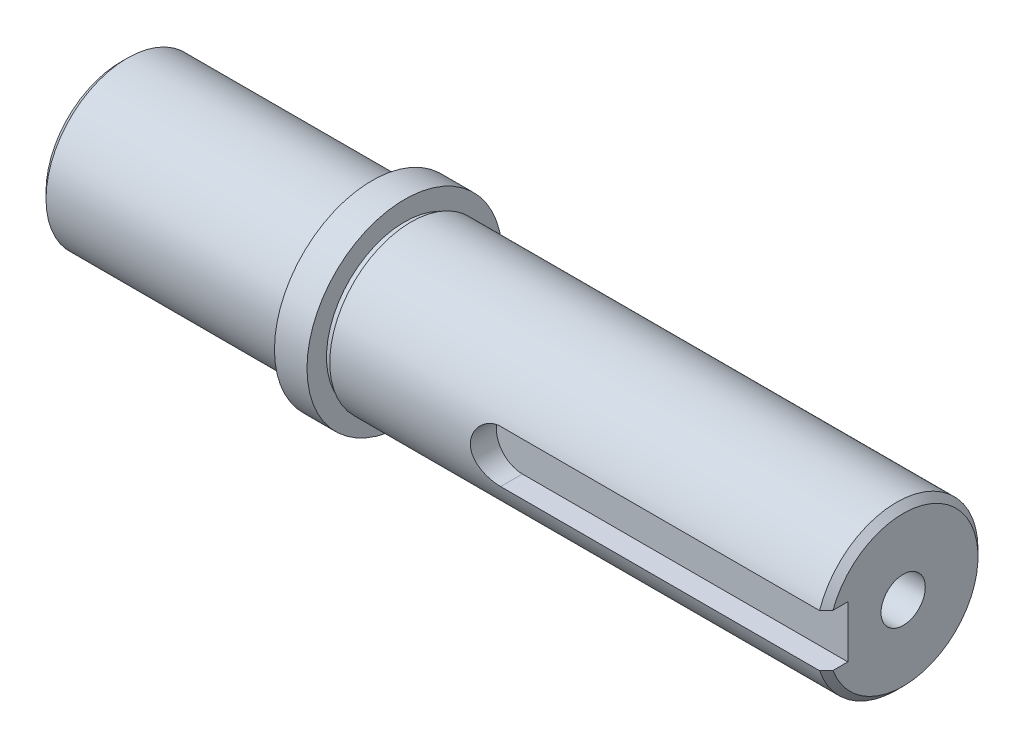
SolidWorks part; units mm, degrees
ref_plane "Plano frontal" through (0, 0, 0) normal (0, 0, 1) x (1, 0, 0)
ref_plane "Plano superior" through (0, 0, 0) normal (0, 1, 0) x (1, 0, 0)
ref_plane "Plano direito" through (0, 0, 0) normal (1, 0, 0) x (0, 0, -1)
sketch "Sketch1" plane through (0, 0, 0) normal (0, 0, 1) x (1, 0, 0)
  line L0 (0, 0) -> (0, 12.5)
  line L1 (0, 12.5) -> (38.6, 12.5)
  line L2 (38.6, 12.5) -> (38.6, 15)
  line L3 (38.6, 15) -> (43.6, 15)
  line L4 (43.6, 15) -> (43.6, 12)
  line L5 (43.6, 12) -> (44.6, 12)
  line L6 (44.6, 12) -> (44.6, 12.5)
  line L7 (44.6, 12.5) -> (120.2, 12.5)
  line L8 (120.2, 12.5) -> (120.2, 0)
  line L9 (120.2, 0) -> (0, 0)
  line L11 (0, 0) -> (-21.8278, 0) construction
  dimension "D1" = 25
  dimension "D2" = 38.6
  dimension "D3" = 5
  dimension "D4" = 1
  dimension "D5" = 24
  dimension "D6" = 76.6
  dimension "D7" = 30
revolve "Revolve1" add sketch "Sketch1" angle 360 about L11
chamfer "Chamfer1" distance 1 angle 45 1 edges at (0, 0, -12.5)
sketch "Sketch2" plane through (120.2, 4.6196, 5.8725) normal (1, 0, 0) x (0, 0, -1)
  line L0 (-6.6275, -4.6196) -> (5.8725, -4.6196) construction
  line L1 (5.8725, -4.6196) -> (5.8725, 7.8804) construction
  circle A0 centre (5.8725, -4.6196) radius 12.5 construction
  circle A2 centre (5.8725, -4.6196) radius 12.5
  dimension "Angle from vertical" = 270
ref_plane "Plane1" through (120.2, 0, 12.5) normal (0, 0, -1) x (-1, 0, 0)
sketch "Sketch3" plane through (120.2, 2.9363, 12.5) normal (0, 0, -1) x (1, 0, 0)
  line L0 (-5, 2.9363) -> (-50, 2.9363) construction
  line L1 (-5, 6.9363) -> (-50, 6.9363)
  line L2 (-5, -1.0637) -> (-50, -1.0637)
  arc A0 (-5, 6.9363) -> (-5, -1.0637) centre (-5, 2.9363) cw
  arc A1 (-50, 6.9363) -> (-50, -1.0637) centre (-50, 2.9363) ccw
  dimension "Keyway width" = 8
  dimension "Distance from end face" = 5
  dimension "Length of slot" = 45
extrude "Cut-Extrude1" cut sketch "Sketch3" along normal blind 4
other "keyway (bs 4235 - part i)<1>"
sketch "Sketch4" plane through (120.2, 0, 0) normal (1, 0, 0) x (0, 0, -1)
  line L0 (-8.5, 4) -> (-11.8427, 4) construction
  line L1 (-8.5, 4) -> (-11.8427, 4)
  line L2 (-8.5, 4) -> (-8.5, -4) construction
  line L3 (-8.5, 4) -> (-8.5, -4)
  line L4 (-8.5, -4) -> (-11.8427, -4) construction
  line L5 (-8.5, -4) -> (-11.8427, -4)
  circle A1 centre (0, 0) radius 12.5
  circle A2 centre (0, 0) radius 12.5
  circle M2 centre (0, 0) radius 12.5
  dimension "D1" = 0
extrude "Cut-Extrude2" cut sketch "Sketch4" against normal blind 10 contours L5 L3 L1 M2
hole_wizard "M8 Tapped Hole1" positions "Sketch6" profile "Sketch5" tap size "M8" standard "DIN"
sketch "Sketch6" plane through (120.2, 0, 0) normal (1, 0, 0) x (0, 0, -1)
  point P0 (0, 0)
sketch "Sketch5" plane through (120.2, 0, 0) normal (0, 1, 0) x (0, 0, -1)
  line L0 (0, 0) -> (0, 21.7929)
  line L1 (0, 21.7929) -> (3.4, 19.75)
  line L2 (3.4, 19.75) -> (3.4, 0)
  line L5 (3.4, 0) -> (0, 0)
  line L10 (0, 21.7929) -> (-3.4, 19.75) construction
  line L11 (0, -6.35) -> (0, 107.95) construction
  dimension "Tap Drill Dia." = 6.8
  dimension "Tap Drill Depth" = 19.75
  dimension "Drill Angle" = 118
cosmetic thread "Hole Thread1" parameters "D1"=16, "D2"=8
chamfer "Chamfer2" distance 1 angle 45 1 edges at (120.2, 0, -12.5)
ref_point "Point1"
